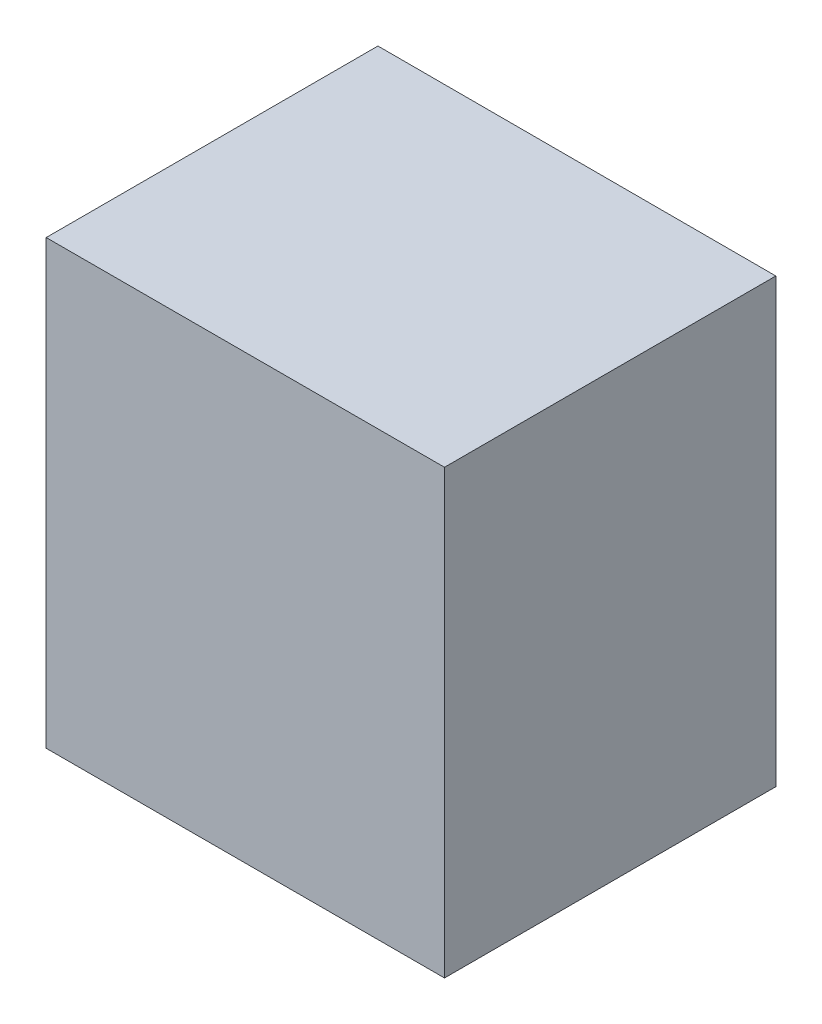
SolidWorks part; units mm, degrees
ref_plane "Front Plane" through (0, 0, 0) normal (0, 0, 1) x (1, 0, 0)
ref_plane "Top Plane" through (0, 0, 0) normal (0, 1, 0) x (1, 0, 0)
ref_plane "Right Plane" through (0, 0, 0) normal (1, 0, 0) x (0, 0, -1)
sketch "Sketch1" plane through (0, 0, 0) normal (0, 1, 0) x (1, 0, 0)
  line L0 (-457.2, 0) -> (457.2, 0) construction
  line L1 (-457.2, -381) -> (-457.2, 381)
  line L2 (0, 1430.6363) -> (0, -1430.6363) construction
  line L3 (-457.2, 381) -> (457.2, 380.492)
  line L4 (457.2, 380.492) -> (457.2, -380.492)
  line L5 (-431.8, -355.092) -> (-431.8, 355.092)
  line L6 (431.8, -355.092) -> (431.8, 355.092)
  line L7 (-431.8, 380.617) -> (-431.8, 355.217) construction
  line L8 (-431.8, 355.217) -> (431.8, 355.092)
  line L9 (-431.8, -355.217) -> (431.8, -355.092)
  line L10 (-457.2, -381) -> (457.2, -380.492)
  point P4 (0, 0)
  point P9 (0, 0)
  point P17 (-431.8, 0)
  point P19 (431.8, 0)
  dimension "D1" = 914.4
  dimension "D2" = 381
  dimension "D3" = 25.4
  dimension "D4" = 25.4
  dimension "D5" = 355.092
  dimension "D6" = 25.4
  dimension "D7" = 355.092
  dimension "D8" = 380.492
extrude "Boss-Extrude1" add sketch "Sketch1" along normal blind 1016
sketch "Sketch2" plane through (0.2115, 0, -380.7459) normal (0.0006, 0, -1) x (-1, 0, -0.0006)
  line L0 (0.2115, 1016) -> (0, 0) construction
  line L2 (-417.3485, 994.2582) -> (417.5615, 994.2582)
  line L3 (-417.3485, 994.2582) -> (-417.3485, 28.9094)
  line L12 (-417.3485, 28.9094) -> (417.5615, 28.9094)
  line L13 (417.5615, 994.2582) -> (417.5615, 28.9094)
  line L14 (-417.3485, 994.2582) -> (417.5615, 28.9094) construction
  line L15 (-417.3485, 28.9094) -> (417.5615, 994.2582) construction
  point P7 (0.1065, 511.5838)
extrude "Cut-Extrude1" cut sketch "Sketch2" against normal blind 723.9
sketch "Sketch3" plane through (-0.1906, 0, 343.154) normal (0.0006, 0, -1) x (-1, 0, -0.0006)
  circle A0 centre (-351.2534, 946.4694) radius 38.1
  dimension "D1" = 76.2
extrude "Boss-Extrude2" add sketch "Sketch3" along normal blind 723.9
sketch "Sketch4" plane through (0.2115, 0, -380.7459) normal (0.0006, 0, -1) x (-1, 0, -0.0006)
  circle A0 centre (-354.2875, 946.2333) radius 21.8245
extrude "Boss-Extrude3" add sketch "Sketch4" along normal blind 3.556
pattern_linear "LPattern4" count 7 spacing 114.3 along (-1, 0, -0.0006) count 9 spacing 104.14 along (0, -1, 0) of "Boss-Extrude2", "Boss-Extrude3"
